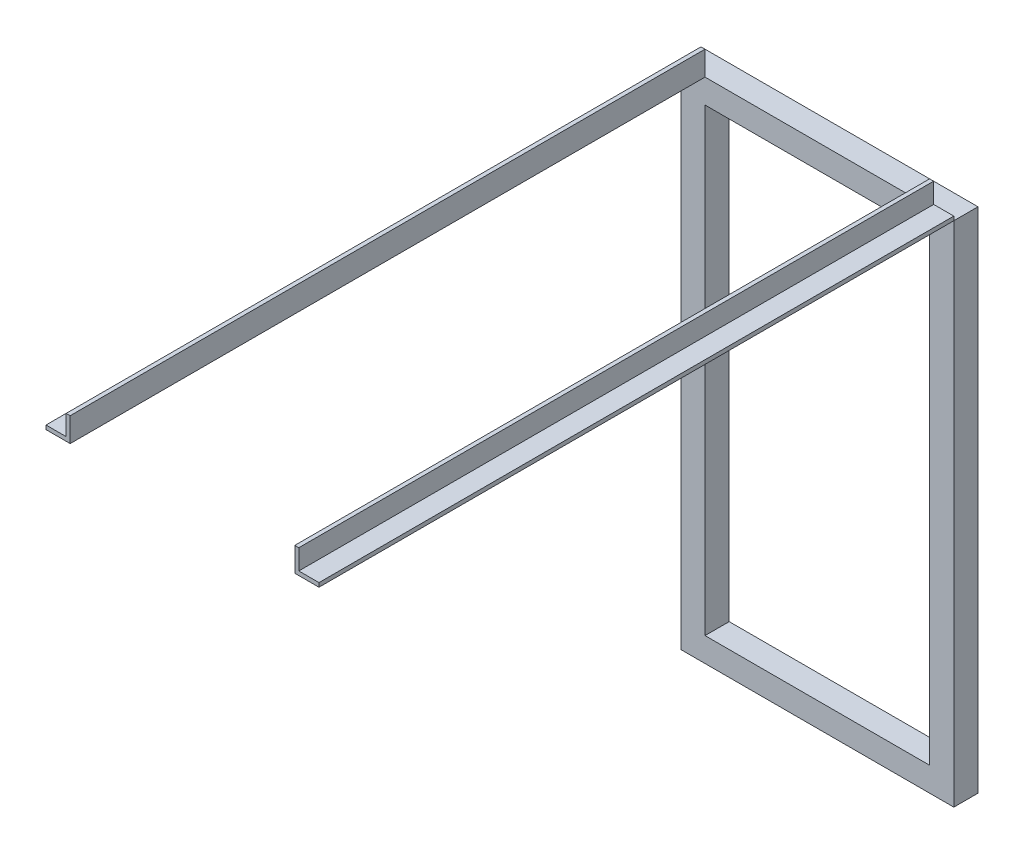
SolidWorks part; units mm, degrees
ref_plane "Alzado" through (0, 0, 0) normal (0, 0, 1) x (1, 0, 0)
ref_plane "Planta" through (0, 0, 0) normal (0, 1, 0) x (1, 0, 0)
ref_plane "Vista lateral" through (0, 0, 0) normal (1, 0, 0) x (0, 0, -1)
sketch "Croquis1" plane through (0, 0, 0) normal (0, 0, 1) x (1, 0, 0)
  line L0 (0, 0) -> (0, 800)
  line L1 (0, 800) -> (430, 800)
  line L2 (430, 800) -> (430, 0)
  line L3 (430, 0) -> (0, 0)
  line L4 (38.1, 761.9) -> (391.9, 761.9)
  line L5 (391.9, 761.9) -> (391.9, 38.1)
  line L6 (391.9, 38.1) -> (38.1, 38.1)
  line L7 (38.1, 38.1) -> (38.1, 761.9)
  dimension "D1" = 800
  dimension "D2" = 430
  dimension "D3" = 38.1
extrude "Saliente-Extruir1" add sketch "Croquis1" along normal blind 38.1
sketch "Croquis3" plane through (0, 0, 38.1) normal (0, 0, 1) x (1, 0, 0)
  line L0 (0, 800) -> (38.1, 800)
  line L1 (430, 800) -> (0, 800) construction
  line L2 (38.1, 800) -> (38.1, 838.1)
  line L3 (215, 800) -> (215, 848.6635) construction
  line L4 (0, 806.35) -> (31.75, 806.35)
  line L5 (31.75, 806.35) -> (31.75, 838.1)
  line L6 (31.75, 838.1) -> (38.1, 838.1)
  line L7 (0, 806.35) -> (0, 800)
  line L8 (398.25, 838.1) -> (391.9, 838.1)
  line L9 (398.25, 806.35) -> (398.25, 838.1)
  line L10 (430, 806.35) -> (398.25, 806.35)
  line L11 (391.9, 800) -> (391.9, 838.1)
  line L12 (430, 800) -> (391.9, 800)
  line L13 (430, 806.35) -> (430, 800)
  dimension "D1" = 38.1
  dimension "D2" = 38.1
  dimension "D3" = 6.35
extrude "Saliente-Extruir2" add sketch "Croquis3" along normal blind 1000 separate body
